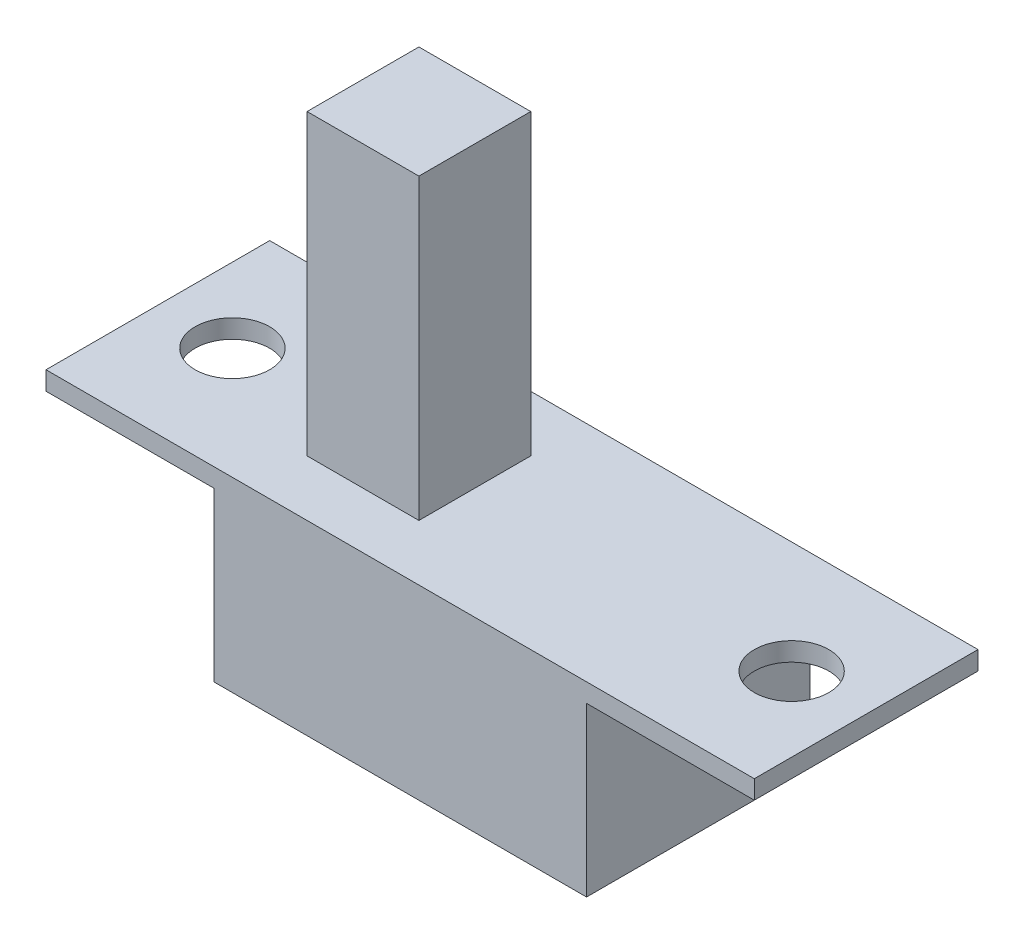
SolidWorks part; units mm, degrees
ref_plane "Front Plane" through (0, 0, 0) normal (0, 0, 1) x (1, 0, 0)
ref_plane "Top Plane" through (0, 0, 0) normal (0, 1, 0) x (1, 0, 0)
ref_plane "Right Plane" through (0, 0, 0) normal (1, 0, 0) x (0, 0, -1)
sketch "Sketch1" plane through (0, 0, 0) normal (0, 1, 0) x (1, 0, 0)
  line L1 (-5, -3) -> (5, -3)
  line L2 (-5, -3) -> (-5, 3)
  line L3 (-5, 3) -> (5, 3)
  line L4 (5, -3) -> (5, 3)
  line L5 (-5, -3) -> (5, 3) construction
  line L6 (-5, 3) -> (5, -3) construction
  point P0 (0, 0)
  dimension "D1" = 10
  dimension "D2" = 6
extrude "Boss-Extrude1" add sketch "Sketch1" along normal blind 5
sketch "Sketch2" plane through (0, 5, 0) normal (0, 1, 0) x (1, 0, 0)
  line L0 (5, 3) -> (-5, 3) construction
  line L1 (-9.5, -3) -> (9.5, -3)
  line L2 (-9.5, -3) -> (-9.5, 3)
  line L3 (-9.5, 3) -> (9.5, 3)
  line L4 (9.5, -3) -> (9.5, 3)
  line L5 (-9.5, -3) -> (9.5, 3) construction
  line L6 (-9.5, 3) -> (9.5, -3) construction
  line L7 (-7.5, 0) -> (-5, 0) construction
  line L8 (-5, 3) -> (-5, -3) construction
  line L9 (-5, 0) -> (5, 0) construction
  line L11 (5, -3) -> (5, 3) construction
  line L13 (5, 0) -> (7.5, 0) construction
  line L14 (7.5, 0) -> (9.5, 0) construction
  line L15 (-7.5, 0) -> (-9.5, 0) construction
  circle A0 centre (-7.5, 0) radius 1
  circle A1 centre (7.5, 0) radius 1
  point P0 (0, 0)
  point P11 (0, 0)
  dimension "D2" = 2
  dimension "D1" = 15
  dimension "D3" = 19
extrude "Boss-Extrude2" add sketch "Sketch2" against normal blind 0.5
sketch "Sketch3" plane through (0, 5, 0) normal (0, 1, 0) x (1, 0, 0)
  line L0 (0, 0) -> (-9.5, 0) construction
  line L1 (-9.5, 3) -> (-9.5, -3) construction
  line L3 (-0.997, -1.5) -> (-3.997, -1.5)
  line L4 (-0.997, -1.5) -> (-0.997, 1.5)
  line L5 (-0.997, 1.5) -> (-3.997, 1.5)
  line L6 (-3.997, -1.5) -> (-3.997, 1.5)
  line L7 (-0.997, -1.5) -> (-3.997, 1.5) construction
  line L8 (-0.997, 1.5) -> (-3.997, -1.5) construction
  line L12 (5, -3) -> (5, 3)
  line L13 (-5, -3) -> (5, -3)
  line L14 (-5, 3) -> (-5, -3)
  line L15 (5, 3) -> (-5, 3)
  line L16 (5, -3) -> (5, 3) construction
  line L17 (-5, -3) -> (5, -3) construction
  line L18 (-5, 3) -> (-5, -3) construction
  line L19 (5, 3) -> (-5, 3) construction
  point P5 (-2.497, 0)
  point P10 (-2.497, 0)
  dimension "D2" = 3
  dimension "D1" = 0
extrude "Boss-Extrude3" add sketch "Sketch3" along normal blind 8
